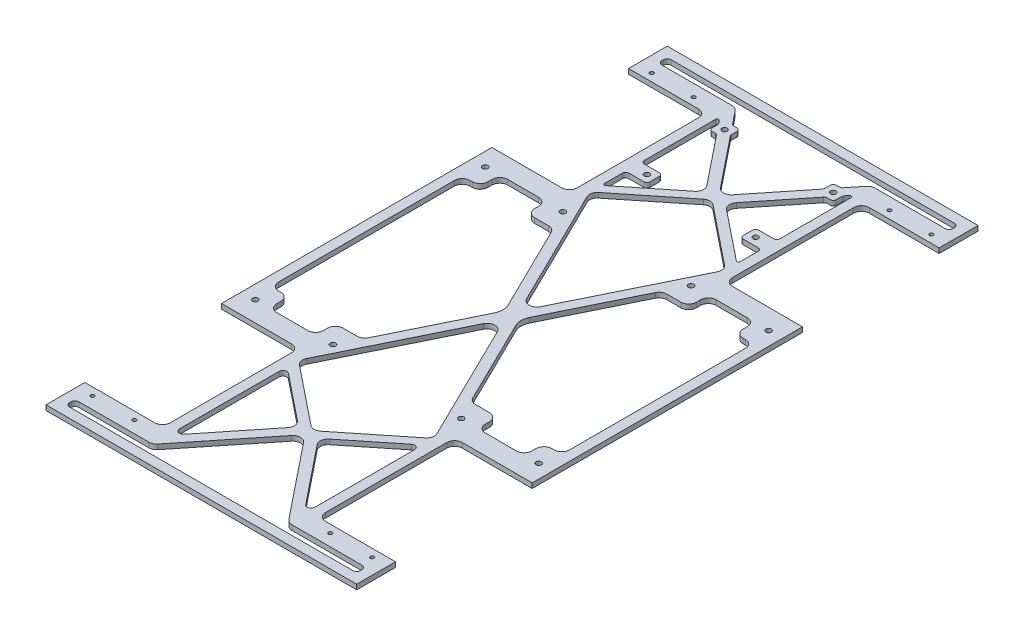
SolidWorks part; units mm, degrees
material "1060 Alloy"
ref_plane "Front Plane" through (0, 0, 0) normal (0, 0, 1) x (1, 0, 0)
ref_plane "Top Plane" through (0, 0, 0) normal (0, 1, 0) x (1, 0, 0)
ref_plane "Right Plane" through (0, 0, 0) normal (1, 0, 0) x (0, 0, -1)
sketch "Sketch1" plane through (0, 0, 0) normal (0, 1, 0) x (1, 0, 0)
  line L0 (-100, 87) -> (-100, -87)
  line L1 (-100, 200) -> (100, 200)
  line L2 (-100, 200) -> (-100, 175)
  line L3 (-100, -200) -> (100, -200)
  line L4 (100, 200) -> (100, 175)
  line L5 (-100, 175) -> (-50, 175)
  line L7 (-100, 87) -> (-50, 87)
  line L8 (-50, 175) -> (-50, 87)
  line L9 (-100, -87) -> (-50, -87)
  line L11 (-100, -175) -> (-50, -175)
  line L12 (-50, -87) -> (-50, -175)
  line L13 (100, -175) -> (50, -175)
  line L15 (100, -87) -> (50, -87)
  line L17 (100, 175) -> (50, 175)
  line L19 (100, 87) -> (50, 87)
  line L20 (50, 175) -> (50, 87)
  line L21 (-100, -175) -> (-100, -200)
  line L22 (100, 87) -> (100, -87)
  line L23 (100, -175) -> (100, -200)
  line L24 (50, -87) -> (50, -175)
  point P4 (0, 200)
  point P6 (100, 0)
  dimension "D1" = 400
  dimension "D2" = 200
  dimension "D3" = 88
  dimension "D4" = 25
  dimension "D5" = 50
extrude "Boss-Extrude1" add sketch "Sketch1" along normal blind 3.175
hole_wizard "3/32 (0.09375) Diameter Hole1" positions "Sketch3" profile "Sketch4" hole size "3/32" standard "ANSI Inch" end condition up to next
sketch "Sketch3" plane through (0, 3.175, 0) normal (0, 1, 0) x (1, 0, 0)
  line L0 (-90, 180) -> (-63.06, 180) construction
  line L5 (-100, 175) -> (-50, 175) construction
  line L6 (-100, 200) -> (-100, 175) construction
  point P0 (-90, 180)
  point P2 (-63.06, 180)
  dimension "D1" = 26.94
  dimension "D2" = 5
  dimension "D3" = 10
  dimension "D4" = 26.94
sketch "Sketch4" plane through (-90, 3.175, -180) normal (1, 0, 0) x (0, 0, 1)
  line L0 (0, 0) -> (0, 3.175)
  line L1 (0, 3.175) -> (1.1906, 3.175)
  line L2 (1.1906, 3.175) -> (1.1906, 0)
  line L5 (1.1906, 0) -> (0, 0)
  line L11 (0, -6.35) -> (0, 107.95) construction
  dimension "Thru Hole Dia." = 2.3812
  dimension "Thru Hole Depth" = 3.175
mirror "Mirror5" about plane through (0, 0, 0) normal (1, 0, 0) of "3/32 (0.09375) Diameter Hole1" second plane through (0, 0, 0) second plane normal (0, 0, 1)
sketch "Sketch5" plane through (0, 3.175, 0) normal (0, 1, 0) x (1, 0, 0)
  line L3 (-34.9422, 61.6) -> (-52.125, 61.6)
  line L4 (-93.65, 61.6) -> (-93.65, 0)
  line L5 (-93.65, 0) -> (-4.7456, 0)
  line L6 (-4.7456, 0) -> (-34.9422, 61.6)
  line L9 (-43.65, 177.5456) -> (-43.65, 101.1091)
  line L10 (-43.65, 101.1091) -> (-6.35, 131)
  line L11 (-6.35, 131) -> (-43.65, 177.5456)
  line L12 (-43.65, 93.79) -> (0, 128.7696)
  line L13 (0, 128.7696) -> (0, 4.7456)
  line L14 (0, 4.7456) -> (-43.65, 93.79)
  line L15 (-93.65, 193.65) -> (-93.65, 187.7)
  line L16 (-93.65, 187.7) -> (-43.65, 187.7)
  line L17 (-43.65, 187.7) -> (0, 133.2304)
  line L18 (0, 133.2304) -> (0, 193.65)
  line L19 (0, 193.65) -> (-93.65, 193.65)
  line L20 (-50, 175) -> (-50, 87) construction
  line L21 (0, 128.7696) -> (0, 133.2304) construction
  line L22 (100, 200) -> (-100, 200) construction
  line L23 (-100, 87) -> (-100, -87) construction
  line L24 (-100, 200) -> (-100, 175) construction
  line L25 (-100, 175) -> (-50, 175) construction
  line L26 (-50, 87) -> (-100, 87) construction
  line L27 (-4.7456, 0) -> (0, 0) construction
  line L28 (0, 0) -> (0, 4.7456) construction
  line L29 (-82.125, 61.6) -> (-93.65, 61.6)
  line L31 (-82.125, 61.6) -> (-82.125, 74.3)
  line L32 (-82.125, 74.3) -> (-52.125, 74.3)
  line L33 (-52.125, 61.6) -> (-52.125, 74.3)
  point P9 (0, 131)
  point P19 (-50, 131)
  dimension "D1" = 6.35
  dimension "D2" = 6.35
  dimension "D3" = 6.35
  dimension "D4" = 6.35
  dimension "D5" = 12.7
  dimension "D6" = 25.4
  dimension "D7" = 6.35
  dimension "D8" = 6.35
  dimension "D9" = 6.35
  dimension "D10" = 12.7
  dimension "D11" = 30
  dimension "D12" = 2.125
extrude "Cut-Extrude1" cut sketch "Sketch5" against normal through all both and the other way through all
mirror "Mirror6" about plane through (0, 0, 0) normal (1, 0, 0) of "Cut-Extrude1" second plane through (0, 0, 0) second plane normal (0, 0, 1)
hole_wizard "Ø3.5 (3.5) Diameter Hole1" positions "Sketch6" profile "Sketch7" hole size "Ø3.5" standard "ANSI Metric" end condition up to next
sketch "Sketch6" plane through (0, 0, 0) normal (0, -1, 0) x (-1, 0, 0)
  line L0 (41.24, 74) -> (91.24, 74) construction
  line L2 (50, 87) -> (100, 87) construction
  line L3 (91.24, 74) -> (100, 74) construction
  line L4 (100, 87) -> (100, -87) construction
  point P0 (41.24, 74)
  point P2 (91.24, 74)
  dimension "D1" = 50
  dimension "D2" = 8.76
  dimension "D3" = 13
sketch "Sketch7" plane through (-41.24, 0, -74) normal (1, 0, 0) x (0, 0, -1)
  line L0 (0, 0) -> (0, 3.175)
  line L1 (0, 3.175) -> (1.75, 3.175)
  line L2 (1.75, 3.175) -> (1.75, 0)
  line L5 (1.75, 0) -> (0, 0)
  line L11 (0, -6.35) -> (0, 107.95) construction
  dimension "Thru Hole Dia." = 3.5
  dimension "Thru Hole Depth" = 3.175
mirror "Mirror7" about plane through (0, 0, 0) normal (1, 0, 0) of "Ø3.5 (3.5) Diameter Hole1" second plane through (0, 0, 0) second plane normal (0, 0, 1)
sketch "Sketch8" plane through (0, 3.175, 0) normal (0, 1, 0) x (1, 0, 0)
  line L0 (-35, 171.8287) -> (35, 171.8287) construction
  line L1 (-40, 116.8287) -> (-30, 116.8287)
  line L3 (-40, 126.8287) -> (-30, 126.8287)
  line L4 (-30, 116.8287) -> (-30, 126.8287)
  line L13 (30, 116.8287) -> (40, 116.8287)
  line L14 (30, 116.8287) -> (30, 126.8287)
  line L15 (30, 126.8287) -> (40, 126.8287)
  line L17 (35, 171.8287) -> (35, 121.8287) construction
  line L18 (35, 121.8287) -> (-35, 121.8287) construction
  line L19 (-35, 121.8287) -> (-35, 171.8287) construction
  line L20 (-40, 166.8287) -> (-40, 176.8287)
  line L21 (-37.4776, 169.8432) -> (-32.5224, 173.8142) construction
  line L23 (-6.35, 131) -> (-43.65, 177.5456) construction
  line L24 (-43.65, 187.7) -> (0, 133.2304) construction
  line L29 (-43.65, 177.5456) -> (-43.65, 101.1091) construction
  line L36 (-40, 166.8287) -> (-30, 166.8287)
  line L38 (-40, 126.8287) -> (-43.65, 126.8287)
  line L41 (30, 166.8287) -> (40, 166.8287)
  line L44 (-40, 176.8287) -> (-30, 176.8287)
  line L45 (-30, 176.8287) -> (-30, 166.8287)
  line L46 (30, 166.8287) -> (30, 176.8287)
  line L47 (30, 176.8287) -> (40, 176.8287)
  line L48 (40, 176.8287) -> (40, 166.8287)
  line L49 (-40, 116.8287) -> (-43.65, 116.8287)
  line L50 (-43.65, 126.8287) -> (-43.65, 116.8287)
  line L51 (43.65, 177.5456) -> (43.65, 101.1091) construction
  line L52 (40, 126.8287) -> (43.65, 126.8287)
  line L54 (40, 116.8287) -> (43.65, 116.8287)
  line L55 (43.65, 126.8287) -> (43.65, 116.8287)
  point P22 (-35, 166.8287)
  point P23 (35, 166.8287)
  point P24 (-35, 126.8287)
  point P25 (30, 121.8287)
  point P26 (35, 126.8287)
  point P27 (-30, 121.8287)
  point P29 (0, 171.8287)
  point P34 (-35, 171.8287)
  dimension "D1" = 10
  dimension "D2" = 10
  dimension "D3" = 70
  dimension "D4" = 50
  dimension "D5" = 10
  dimension "D6" = 10
  dimension "D7" = 5
  dimension "D8" = 10
  dimension "D9" = 13.65
  dimension "D10" = 13.65
extrude "Boss-Extrude2" add sketch "Sketch8" against normal up to surface (3.175 mm away) up to face at (61.4562, 0, 0)
hole_wizard "M3 Clearance Hole1" positions "Sketch9" profile "Sketch10" hole size "M3" standard "ANSI Metric" end condition up to next
sketch "Sketch9" plane through (0, 3.175, 0) normal (0, 1, 0) x (1, 0, 0)
  line L0 (-35, 171.8287) -> (35, 171.8287) construction
  line L1 (35, 171.8287) -> (35, 121.8287) construction
  line L2 (35, 121.8287) -> (-35, 121.8287) construction
  line L3 (-35, 121.8287) -> (-35, 171.8287) construction
  line L6 (-30, 176.8287) -> (-34.9381, 176.8287) construction
  point P0 (-35, 171.8287)
  point P2 (35, 171.8287)
  point P4 (35, 121.8287)
  point P6 (-35, 121.8287)
  point P19 (0, 121.8287)
  dimension "D1" = 70
  dimension "D2" = 50
  dimension "D3" = 5
sketch "Sketch10" plane through (-35, 3.175, -171.8287) normal (1, 0, 0) x (0, 0, 1)
  line L0 (0, 0) -> (0, 3.175)
  line L1 (0, 3.175) -> (1.7, 3.175)
  line L2 (1.7, 3.175) -> (1.7, 0)
  line L5 (1.7, 0) -> (0, 0)
  line L11 (0, -6.35) -> (0, 107.95) construction
  dimension "Thru Hole Dia." = 3.4
  dimension "Thru Hole Depth" = 3.175
sketch "Sketch11" [suppressed] plane through (0, 3.175, 0) normal (0, 1, 0) x (1, 0, 0)
  line L1 (-43.65, 187.7) -> (43.65, 187.7)
  line L2 (-43.65, 187.7) -> (-43.65, 94.2145)
  line L3 (-43.65, 94.2145) -> (43.65, 94.2145)
  line L4 (43.65, 187.7) -> (43.65, 94.2145)
extrude "Cut-Extrude2" [suppressed] cut sketch "Sketch11" against normal up to surface (3.175 mm away)
sketch "Sketch12" [suppressed] plane through (0, 3.175, 0) normal (0, 1, 0) x (1, 0, 0)
  line L0 (-100, -200) -> (100, -200) construction
  line L1 (-32.5, -105) -> (32.5, -105)
  line L2 (-32.5, -105) -> (-32.5, -190)
  line L3 (-32.5, -190) -> (32.5, -190)
  line L4 (32.5, -105) -> (32.5, -190)
  point P5 (0, -190)
  dimension "D1" = 65
  dimension "D2" = 85
  dimension "D3" = 10
extrude "Cut-Extrude3" [suppressed] cut sketch "Sketch12" against normal up to surface (3.175 mm away)
fillet "Fillet1" radius 5 38 edges at (-34.9422, 1.5875, -61.6) (-93.65, 1.5875, -61.6) (-82.125, 1.5875, -61.6) (-82.125, 1.5875, -74.3) (-52.125, 1.5875, -74.3) (-52.125, 1.5875, -61.6) (-34.9422, 1.5875, 61.6) (-52.125, 1.5875, 61.6) (-52.125, 1.5875, 74.3) (-82.125, 1.5875, 74.3) (-82.125, 1.5875, 61.6) (-93.65, 1.5875, 61.6) (-6.35, 1.5875, 131) (-43.65, 1.5875, 93.79) (0, 1.5875, 128.7696) (-43.65, 1.5875, 187.7) (0, 1.5875, 133.2304) (34.9422, 1.5875, -61.6) (52.125, 1.5875, -61.6) (52.125, 1.5875, -74.3) (82.125, 1.5875, -74.3) (82.125, 1.5875, -61.6) (93.65, 1.5875, -61.6) (93.65, 1.5875, 61.6) (82.125, 1.5875, 61.6) (82.125, 1.5875, 74.3) (52.125, 1.5875, 74.3) (52.125, 1.5875, 61.6) (34.9422, 1.5875, 61.6) (6.35, 1.5875, 131) (43.65, 1.5875, 93.79) (43.65, 1.5875, 187.7)
fillet "Fillet2" radius 10 2 edges at (-4.7456, 1.5875, 0) (4.7456, 1.5875, 0)
fillet "Fillet3" radius 2.5 12 edges at (-93.65, 1.5875, -193.65) (-93.65, 1.5875, -187.7) (-43.65, 1.5875, 177.5456) (-43.65, 1.5875, 101.1091) (-93.65, 1.5875, 193.65) (-93.65, 1.5875, 187.7) (93.65, 1.5875, -193.65) (93.65, 1.5875, -187.7) (43.65, 1.5875, 177.5456) (43.65, 1.5875, 101.1091) (93.65, 1.5875, 187.7) (93.65, 1.5875, 193.65)
fillet "Fillet4" [suppressed] radius 5
fillet "Fillet5" radius 5 14 edges at (-43.65, 1.5875, -93.79) (-43.65, 1.5875, -187.7) (50, 1.5875, -175) (50, 1.5875, -87) (50, 1.5875, 87) (50, 1.5875, 175) (-50, 1.5875, 175) (-50, 1.5875, 87) (43.65, 1.5875, -93.79) (-50, 1.5875, -87) (-50, 1.5875, -175) (43.65, 1.5875, -187.7)
fillet "Fillet6" radius 5 4 edges at (-6.35, 1.5875, -131) (0, 1.5875, -128.7696) (0, 1.5875, -133.2304) (6.35, 1.5875, -131)
fillet "Fillet7" radius 2 20 edges at (-43.65, 1.5875, -116.8287) (-43.65, 1.5875, -126.8287) (-30, 1.5875, -126.8287) (-30, 1.5875, -116.8287) (-40, 1.5875, -172.9909) (-35.0619, 1.5875, -166.8287) (-34.9381, 1.5875, -176.8287) (-30, 1.5875, -170.6666) (-30, 1.5875, -176.8287) (-40, 1.5875, -166.8287) (35.0619, 1.5875, -166.8287) (40, 1.5875, -172.9909) (30, 1.5875, -170.6666) (34.9381, 1.5875, -176.8287) (30, 1.5875, -176.8287) (40, 1.5875, -166.8287) (30, 1.5875, -116.8287) (30, 1.5875, -126.8287) (43.65, 1.5875, -126.8287) (43.65, 1.5875, -116.8287)
fillet "Fillet8" radius 1 4 edges at (-43.65, 1.5875, -177.5456) (-43.65, 1.5875, -101.1091) (43.65, 1.5875, -177.5456) (43.65, 1.5875, -101.1091)
